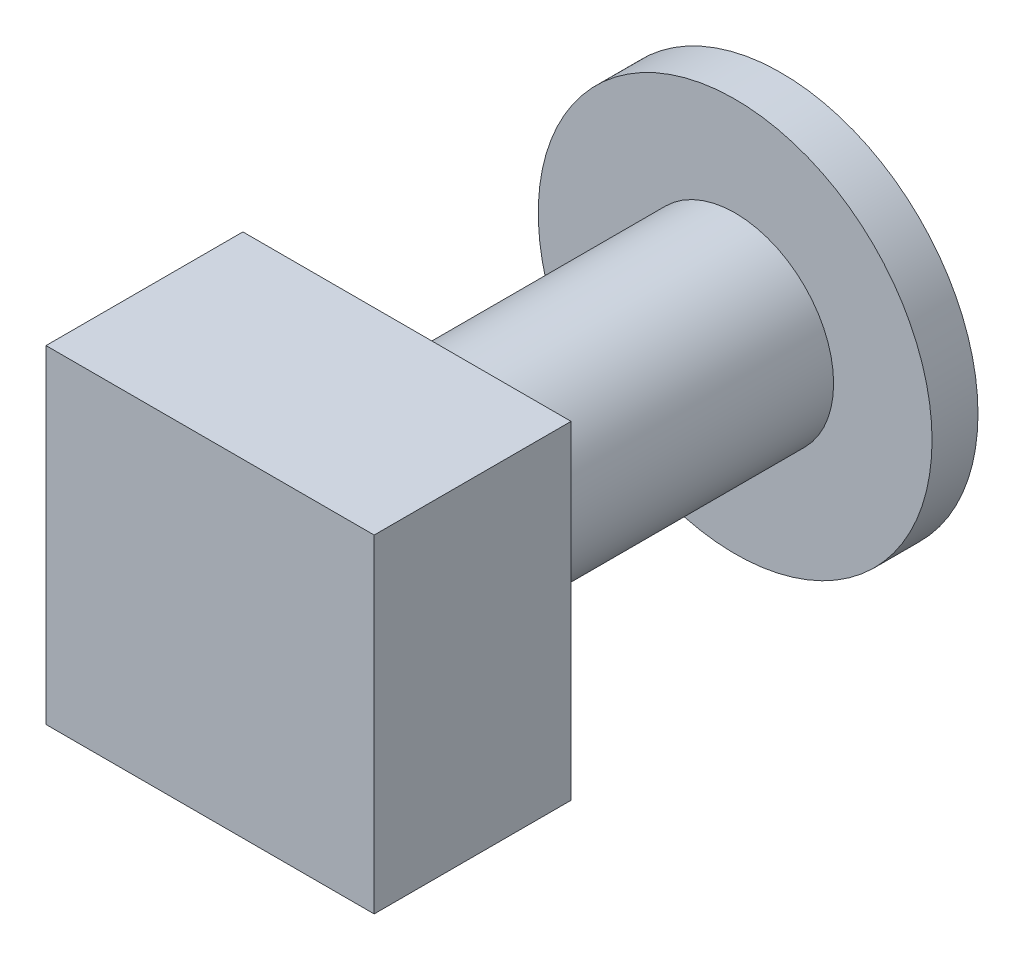
SolidWorks part; units mm, degrees
ref_plane "정면" through (0, 0, 0) normal (0, 0, 1) x (1, 0, 0)
ref_plane "윗면" through (0, 0, 0) normal (0, 1, 0) x (1, 0, 0)
ref_plane "우측면" through (0, 0, 0) normal (1, 0, 0) x (0, 0, -1)
sketch "스케치1" plane through (0, 0, 0) normal (0, 0, 1) x (1, 0, 0)
  circle A0 centre (0, 0) radius 30
  dimension "D1" = 60
extrude "보스-돌출1" add sketch "스케치1" along normal blind 7 contours A0
sketch "스케치2" plane through (0, 0, 7) normal (0, 0, 1) x (1, 0, 0)
  circle A0 centre (0, 0) radius 15
  dimension "D1" = 30
extrude "보스-돌출2" add sketch "스케치2" along normal blind 50
sketch "스케치3" plane through (0, 0, 57) normal (0, 0, 1) x (1, 0, 0)
  line L1 (-25, -25) -> (25, -25)
  line L2 (-25, -25) -> (-25, 25)
  line L3 (-25, 25) -> (25, 25)
  line L4 (25, -25) -> (25, 25)
  line L5 (0, 25) -> (0, -25) construction
  line L6 (-25, 0) -> (25, 0) construction
  point P0 (0, 0)
  dimension "D1" = 50
  dimension "D2" = 50
extrude "보스-돌출3" add sketch "스케치3" along normal blind 30
sketch3d "URDF Reference"
  line L0 (0, 0, 0) -> (10, 0, 0) construction
  line L1 (0, 0, 0) -> (0, 0, -10) construction
  point P0 (0, 0, 0)
  point P1 (0, 0, 0)
